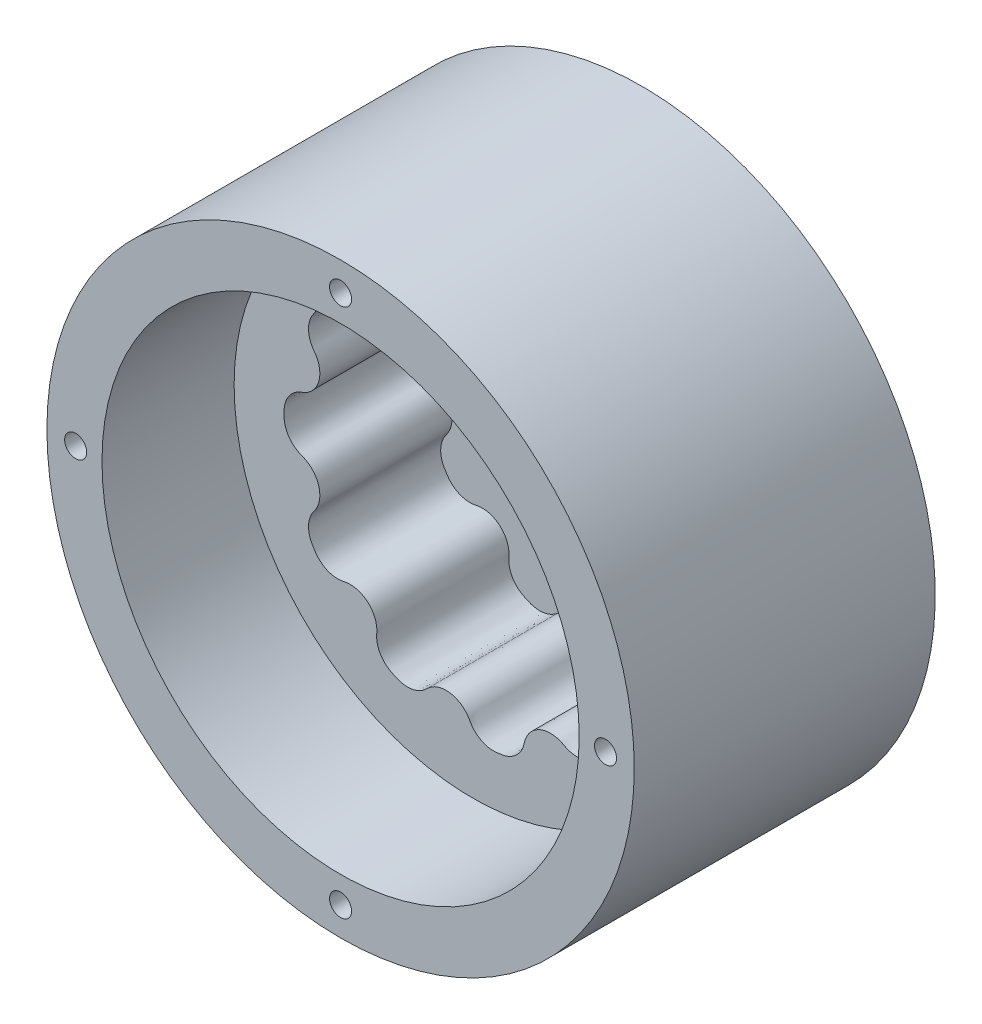
SolidWorks part; units mm, degrees
material "ABS PC"
ref_plane "Front Plane" through (0, 0, 0) normal (0, 0, 1) x (1, 0, 0)
ref_plane "Top Plane" through (0, 0, 0) normal (0, 1, 0) x (1, 0, 0)
ref_plane "Right Plane" through (0, 0, 0) normal (1, 0, 0) x (0, 0, -1)
sketch "Sketch1" plane through (0, 0, 0) normal (0, 0, 1) x (1, 0, 0)
  circle A0 centre (0, 0) radius 35.5
  spline S0 degree 3 poles (3.8373, 25.4119) (3.7175, 25.43) (3.5976, 25.4472) (3.4775, 25.4636) (3.4374, 25.4691) (3.3572, 25.4799) (3.2368, 25.4956) (3.1563, 25.5033) (3.1159, 25.5065) (1.7329, 25.6153) (0.4925, 24.9939) (-0.2484, 23.821) (-0.2845, 23.7639) (-0.3534, 23.6478) (-0.4463, 23.4675) (-0.5152, 23.3514) (-0.5513, 23.2943) (-1.8392, 21.2577) (-4.2243, 20.9147) (-6.0338, 22.5061) (-6.0845, 22.5506) (-6.1834, 22.6426) (-6.3233, 22.7894) (-6.4221, 22.8815) (-6.4728, 22.9261) (-7.5142, 23.8428) (-8.8794, 24.0895) (-10.1757, 23.5954) (-10.2135, 23.581) (-10.2887, 23.5509) (-10.3998, 23.5019) (-10.4737, 23.469) (-10.5106, 23.4524) (-10.6212, 23.4029) (-10.7314, 23.3526) (-10.8412, 23.3015) (-10.8779, 23.2844) (-10.9512, 23.2501) (-11.061, 23.1982) (-11.1329, 23.1611) (-11.1685, 23.142) (-12.3909, 22.4859) (-13.0984, 21.2925) (-13.0876, 19.9052) (-13.0871, 19.8377) (-13.0823, 19.7027) (-13.0629, 19.5009) (-13.0582, 19.3659) (-13.0577, 19.2984) (-13.04, 16.8887) (-14.8611, 15.3108) (-17.2436, 15.6712) (-17.3104, 15.6813) (-17.4433, 15.7052) (-17.6404, 15.7531) (-17.7733, 15.7771) (-17.84, 15.7872) (-19.2117, 15.9953) (-20.4936, 15.4648) (-21.317, 14.3483) (-21.341, 14.3157) (-21.388, 14.2498) (-21.4549, 14.1485) (-21.4993, 14.0809) (-21.5214, 14.047) (-21.5876, 13.9455) (-21.6531, 13.8436) (-21.7179, 13.7412) (-21.7396, 13.7071) (-21.7827, 13.6386) (-21.847, 13.5356) (-21.8874, 13.4655) (-21.9071, 13.4301) (-22.5807, 12.2173) (-22.5307, 10.8309) (-21.7716, 9.6696) (-21.7346, 9.6131) (-21.6576, 9.5022) (-21.5322, 9.3428) (-21.4552, 9.2318) (-21.4183, 9.1753) (-20.1007, 7.1578) (-20.7795, 4.8457) (-22.9787, 3.8608) (-23.0404, 3.8332) (-23.1651, 3.7815) (-23.3568, 3.7152) (-23.4816, 3.6635) (-23.5432, 3.636) (-24.8096, 3.0695) (-25.6012, 1.9302) (-25.6903, 0.5457) (-25.6929, 0.5053) (-25.6967, 0.4245) (-25.6983, 0.3031) (-25.6991, 0.2222) (-25.6994, 0.1817) (-25.7002, 0.0606) (-25.7002, -0.0606) (-25.6994, -0.1817) (-25.6991, -0.2222) (-25.6983, -0.3031) (-25.6967, -0.4245) (-25.6929, -0.5053) (-25.6903, -0.5457) (-25.6012, -1.9302) (-24.8096, -3.0695) (-23.5432, -3.636) (-23.4816, -3.6635) (-23.3568, -3.7152) (-23.1651, -3.7815) (-23.0404, -3.8332) (-22.9787, -3.8608) (-20.7795, -4.8457) (-20.1007, -7.1578) (-21.4183, -9.1753) (-21.4552, -9.2318) (-21.5322, -9.3428) (-21.6576, -9.5022) (-21.7346, -9.6131) (-21.7716, -9.6696) (-22.5307, -10.8309) (-22.5807, -12.2173) (-21.9071, -13.4301) (-21.8874, -13.4655) (-21.847, -13.5356) (-21.7827, -13.6386) (-21.7396, -13.7071) (-21.7179, -13.7412) (-21.6531, -13.8436) (-21.5876, -13.9455) (-21.5214, -14.047) (-21.4993, -14.0809) (-21.4549, -14.1485) (-21.388, -14.2498) (-21.341, -14.3157) (-21.317, -14.3483) (-20.4936, -15.4648) (-19.2117, -15.9953) (-17.84, -15.7872) (-17.7733, -15.7771) (-17.6404, -15.7531) (-17.4433, -15.7052) (-17.3104, -15.6813) (-17.2436, -15.6712) (-14.8611, -15.3108) (-13.04, -16.8887) (-13.0577, -19.2984) (-13.0582, -19.3659) (-13.0629, -19.5009) (-13.0823, -19.7027) (-13.0871, -19.8377) (-13.0876, -19.9052) (-13.0984, -21.2925) (-12.3909, -22.4859) (-11.1685, -23.142) (-11.1329, -23.1611) (-11.061, -23.1982) (-10.9512, -23.2501) (-10.8779, -23.2844) (-10.8412, -23.3015) (-10.7314, -23.3526) (-10.6212, -23.4029) (-10.5106, -23.4524) (-10.4737, -23.469) (-10.3998, -23.5019) (-10.2887, -23.5509) (-10.2135, -23.581) (-10.1757, -23.5954) (-8.8794, -24.0895) (-7.5142, -23.8428) (-6.4728, -22.9261) (-6.4221, -22.8815) (-6.3233, -22.7894) (-6.1834, -22.6426) (-6.0845, -22.5506) (-6.0338, -22.5061) (-4.2243, -20.9147) (-1.8392, -21.2577) (-0.5513, -23.2943) (-0.5152, -23.3514) (-0.4463, -23.4675) (-0.3534, -23.6478) (-0.2845, -23.7639) (-0.2484, -23.821) (0.4925, -24.9939) (1.7329, -25.6153) (3.1159, -25.5065) (3.1563, -25.5033) (3.2368, -25.4956) (3.3572, -25.4799) (3.4374, -25.4691) (3.4775, -25.4636) (3.5976, -25.4472) (3.7175, -25.43) (3.8373, -25.4119) (3.8773, -25.4059) (3.9573, -25.3936) (4.0772, -25.3748) (4.1567, -25.3594) (4.1963, -25.3511) (5.554, -25.0659) (6.5691, -24.1203) (6.9495, -22.7861) (6.968, -22.7212) (7.0014, -22.5903) (7.0397, -22.3912) (7.0732, -22.2603) (7.0918, -22.1954) (7.7536, -19.8784) (9.9456, -18.8774) (12.1301, -19.8945) (12.1913, -19.923) (12.3121, -19.9834) (12.4877, -20.0848) (12.6084, -20.1453) (12.6696, -20.1738) (13.9271, -20.76) (15.3065, -20.6121) (16.4111, -19.7728) (16.4433, -19.7483) (16.507, -19.6983) (16.5998, -19.62) (16.6614, -19.5676) (16.6922, -19.5413) (16.7843, -19.4626) (16.8758, -19.3833) (16.9668, -19.3033) (16.9972, -19.2766) (17.0579, -19.223) (17.1486, -19.1423) (17.2072, -19.0865) (17.236, -19.0581) (18.224, -18.0841) (18.5666, -16.7398) (18.1654, -15.4117) (18.1459, -15.3471) (18.1032, -15.2189) (18.0278, -15.0307) (17.9852, -14.9025) (17.9657, -14.8379) (17.2699, -12.5309) (18.5726, -10.5037) (20.9602, -10.1783) (21.0271, -10.1692) (21.1614, -10.1547) (21.364, -10.1451) (21.4983, -10.1307) (21.5652, -10.1216) (22.9399, -9.9349) (24.0204, -9.0647) (24.4959, -7.7614) (24.5098, -7.7234) (24.5362, -7.6469) (24.572, -7.5309) (24.5955, -7.4534) (24.6072, -7.4147) (24.6421, -7.2987) (24.6762, -7.1825) (24.7096, -7.066) (24.7207, -7.0271) (24.7427, -6.9492) (24.7754, -6.8323) (24.7945, -6.7536) (24.8034, -6.7142) (25.108, -5.3607) (24.6694, -4.0445) (23.6139, -3.1442) (23.5625, -3.1004) (23.4574, -3.0156) (23.2921, -2.8981) (23.187, -2.8133) (23.1357, -2.7694) (21.303, -1.2048) (21.303, 1.2048) (23.1357, 2.7694) (23.187, 2.8133) (23.2921, 2.8981) (23.4574, 3.0156) (23.5625, 3.1004) (23.6139, 3.1442) (24.6694, 4.0445) (25.108, 5.3607) (24.8034, 6.7142) (24.7945, 6.7536) (24.7754, 6.8323) (24.7427, 6.9492) (24.7207, 7.0271) (24.7096, 7.066) (24.6762, 7.1825) (24.6421, 7.2987) (24.6072, 7.4147) (24.5955, 7.4534) (24.572, 7.5309) (24.5362, 7.6469) (24.5098, 7.7234) (24.4959, 7.7614) (24.0204, 9.0647) (22.9399, 9.9349) (21.5652, 10.1216) (21.4983, 10.1307) (21.364, 10.1451) (21.1614, 10.1547) (21.0271, 10.1692) (20.9602, 10.1783) (18.5726, 10.5037) (17.2699, 12.5309) (17.9657, 14.8379) (17.9852, 14.9025) (18.0278, 15.0307) (18.1032, 15.2189) (18.1459, 15.3471) (18.1654, 15.4117) (18.5666, 16.7398) (18.224, 18.0841) (17.236, 19.0581) (17.2072, 19.0865) (17.1486, 19.1423) (17.0579, 19.223) (16.9972, 19.2766) (16.9668, 19.3033) (16.8758, 19.3833) (16.7843, 19.4626) (16.6922, 19.5413) (16.6614, 19.5676) (16.5998, 19.62) (16.507, 19.6983) (16.4433, 19.7483) (16.4111, 19.7728) (15.3065, 20.6121) (13.9271, 20.76) (12.6696, 20.1738) (12.6084, 20.1453) (12.4877, 20.0848) (12.3121, 19.9834) (12.1913, 19.923) (12.1301, 19.8945) (9.9456, 18.8774) (7.7536, 19.8784) (7.0918, 22.1954) (7.0732, 22.2603) (7.0397, 22.3912) (7.0014, 22.5903) (6.968, 22.7212) (6.9495, 22.7861) (6.5691, 24.1203) (5.554, 25.0659) (4.1963, 25.3511) (4.1567, 25.3594) (4.0772, 25.3748) (3.9573, 25.3936) (3.8773, 25.4059) (3.8373, 25.4119) (3.7175, 25.43) (3.5976, 25.4472) knots -0.000718 0 0 0 0.002149 0.002149 0.002149 0.002867 0.003585 0.004303 0.004303 0.004303 0.026557 0.026557 0.026557 0.027755 0.028953 0.030151 0.030151 0.030151 0.062908 0.062908 0.062908 0.064106 0.065304 0.066501 0.066501 0.066501 0.088756 0.088756 0.088756 0.089474 0.090191 0.090909 0.090909 0.090909 0.093059 0.093059 0.093059 0.093776 0.094494 0.095212 0.095212 0.095212 0.117466 0.117466 0.117466 0.118664 0.119862 0.12106 0.12106 0.12106 0.153817 0.153817 0.153817 0.155015 0.156213 0.15741 0.15741 0.15741 0.179665 0.179665 0.179665 0.180383 0.1811 0.181818 0.181818 0.181818 0.183968 0.183968 0.183968 0.184685 0.185403 0.186121 0.186121 0.186121 0.208375 0.208375 0.208375 0.209573 0.210771 0.211969 0.211969 0.211969 0.244726 0.244726 0.244726 0.245924 0.247122 0.24832 0.24832 0.24832 0.270574 0.270574 0.270574 0.271292 0.272009 0.272727 0.272727 0.272727 0.274877 0.274877 0.274877 0.275595 0.276312 0.27703 0.27703 0.27703 0.299285 0.299285 0.299285 0.300482 0.30168 0.302878 0.302878 0.302878 0.335635 0.335635 0.335635 0.336833 0.338031 0.339229 0.339229 0.339229 0.361483 0.361483 0.361483 0.362201 0.362919 0.363636 0.363636 0.363636 0.365786 0.365786 0.365786 0.366504 0.367221 0.367939 0.367939 0.367939 0.390194 0.390194 0.390194 0.391391 0.392589 0.393787 0.393787 0.393787 0.426544 0.426544 0.426544 0.427742 0.42894 0.430138 0.430138 0.430138 0.452392 0.452392 0.452392 0.45311 0.453828 0.454545 0.454545 0.454545 0.456695 0.456695 0.456695 0.457413 0.458131 0.458848 0.458848 0.458848 0.481103 0.481103 0.481103 0.4823 0.483498 0.484696 0.484696 0.484696 0.517453 0.517453 0.517453 0.518651 0.519849 0.521047 0.521047 0.521047 0.543301 0.543301 0.543301 0.544019 0.544737 0.545455 0.545455 0.545455 0.547604 0.547604 0.547604 0.548322 0.54904 0.549757 0.549757 0.549757 0.572012 0.572012 0.572012 0.57321 0.574407 0.575605 0.575605 0.575605 0.608362 0.608362 0.608362 0.60956 0.610758 0.611956 0.611956 0.611956 0.63421 0.63421 0.63421 0.634928 0.635646 0.636364 0.636364 0.636364 0.638513 0.638513 0.638513 0.639231 0.639949 0.640666 0.640666 0.640666 0.662921 0.662921 0.662921 0.664119 0.665316 0.666514 0.666514 0.666514 0.699272 0.699272 0.699272 0.700469 0.701667 0.702865 0.702865 0.702865 0.725119 0.725119 0.725119 0.725837 0.726555 0.727273 0.727273 0.727273 0.729422 0.729422 0.729422 0.73014 0.730858 0.731576 0.731576 0.731576 0.75383 0.75383 0.75383 0.755028 0.756226 0.757423 0.757423 0.757423 0.790181 0.790181 0.790181 0.791378 0.792576 0.793774 0.793774 0.793774 0.816028 0.816028 0.816028 0.816746 0.817464 0.818182 0.818182 0.818182 0.820331 0.820331 0.820331 0.821049 0.821767 0.822485 0.822485 0.822485 0.844739 0.844739 0.844739 0.845937 0.847135 0.848332 0.848332 0.848332 0.88109 0.88109 0.88109 0.882288 0.883485 0.884683 0.884683 0.884683 0.906938 0.906938 0.906938 0.907655 0.908373 0.909091 0.909091 0.909091 0.91124 0.91124 0.91124 0.911958 0.912676 0.913394 0.913394 0.913394 0.935648 0.935648 0.935648 0.936846 0.938044 0.939242 0.939242 0.939242 0.971999 0.971999 0.971999 0.973197 0.974394 0.975592 0.975592 0.975592 0.997847 0.997847 0.997847 0.998564 0.999282 1 1 1 1.002149 1.002149 1.002149 weights 1 0.999983 0.999983 1 1 1 1 1 1 0.904116 0.904116 1 1 1 1 1 1 0.766196 0.766196 1 1 1 1 1 1 0.904116 0.904116 1 1 1 1 1 1 0.999983 0.999983 1 1 1 1 1 1 0.904116 0.904116 1 1 1 1 1 1 0.766196 0.766196 1 1 1 1 1 1 0.904116 0.904116 1 1 1 1 1 1 0.999983 0.999983 1 1 1 1 1 1 0.904116 0.904116 1 1 1 1 1 1 0.766196 0.766196 1 1 1 1 1 1 0.904116 0.904116 1 1 1 1 1 1 0.999983 0.999983 1 1 1 1 1 1 0.904116 0.904116 1 1 1 1 1 1 0.766196 0.766196 1 1 1 1 1 1 0.904116 0.904116 1 1 1 1 1 1 0.999983 0.999983 1 1 1 1 1 1 0.904116 0.904116 1 1 1 1 1 1 0.766196 0.766196 1 1 1 1 1 1 0.904116 0.904116 1 1 1 1 1 1 0.999983 0.999983 1 1 1 1 1 1 0.904116 0.904116 1 1 1 1 1 1 0.766196 0.766196 1 1 1 1 1 1 0.904116 0.904116 1 1 1 1 1 1 0.999983 0.999983 1 1 1 1 1 1 0.904116 0.904116 1 1 1 1 1 1 0.766196 0.766196 1 1 1 1 1 1 0.904116 0.904116 1 1 1 1 1 1 0.999983 0.999983 1 1 1 1 1 1 0.904116 0.904116 1 1 1 1 1 1 0.766196 0.766196 1 1 1 1 1 1 0.904116 0.904116 1 1 1 1 1 1 0.999983 0.999983 1 1 1 1 1 1 0.904116 0.904116 1 1 1 1 1 1 0.766196 0.766196 1 1 1 1 1 1 0.904116 0.904116 1 1 1 1 1 1 0.999983 0.999983 1 1 1 1 1 1 0.904116 0.904116 1 1 1 1 1 1 0.766196 0.766196 1 1 1 1 1 1 0.904116 0.904116 1 1 1 1 1 1 0.999983 0.999983 1 1 1 1 1 1 0.904116 0.904116 1 1 1 1 1 1 0.766196 0.766196 1 1 1 1 1 1 0.904116 0.904116 1 1 1 1 1 1 0.999983 0.999983 only from (3.8373, 25.4119) to (3.8373, 25.4119)
  dimension "D1" = 25.7
extrude "Boss-Extrude1" add sketch "Sketch1" along normal blind 18
sketch "Sketch2" plane through (0, 0, 18) normal (0, 0, 1) x (1, 0, 0)
  circle A0 centre (0, 0) radius 32.5
  circle A1 centre (0, 0) radius 40
  dimension "D1" = 65
  dimension "D2" = 80
extrude "Boss-Extrude4" add sketch "Sketch2" along normal blind 36 from offset 18
sketch "Sketch5" plane through (0, 0, 0) normal (0, 0, -1) x (-1, 0, 0)
  circle A0 centre (0, 0) radius 40
  circle A1 centre (0, 0) radius 14
  dimension "D1" = 28
extrude "Boss-Extrude5" add sketch "Sketch5" along normal blind 5
sketch "Sketch6" plane through (0, 0, 36) normal (0, 0, 1) x (1, 0, 0)
  circle A0 centre (0, 36.0854) radius 1.5
  circle A1 centre (36.0854, 0) radius 1.5
  circle A2 centre (0, -36.0854) radius 1.5
  circle A3 centre (-36.0854, 0) radius 1.5
  point P11 (0, 0)
  dimension "D1" = 3
  dimension "D2" = 4
extrude "Cut-Extrude1" cut sketch "Sketch6" against normal blind 8
